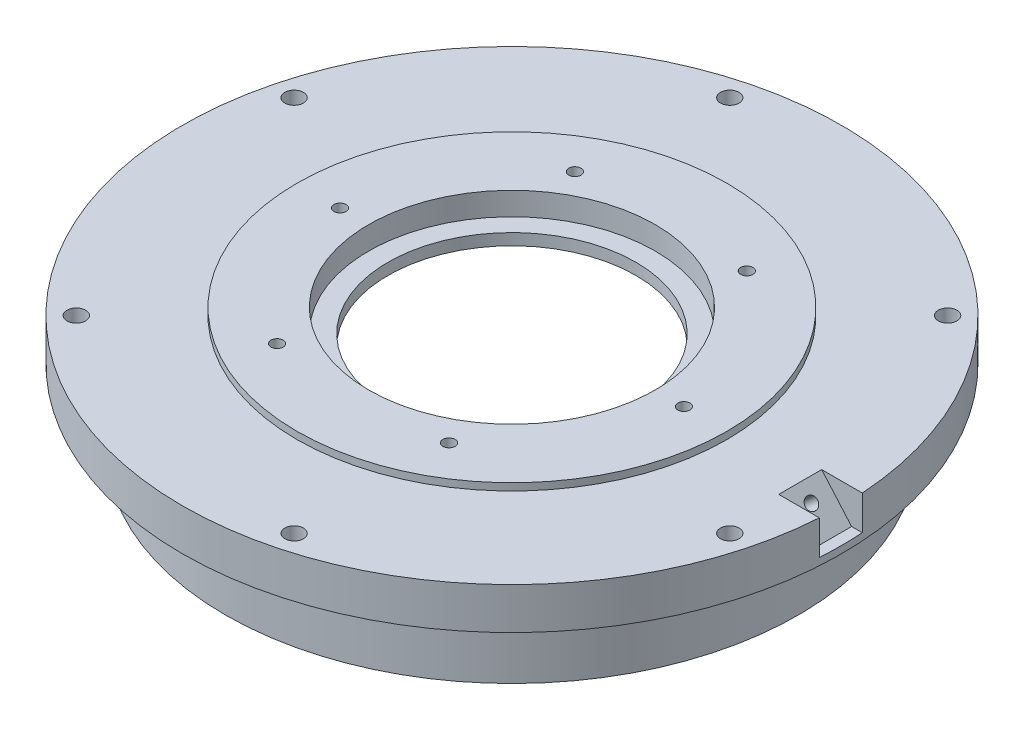
SolidWorks part; units mm, degrees
ref_plane "前视基准面" through (0, 0, 0) normal (0, 0, 1) x (1, 0, 0)
ref_plane "上视基准面" through (0, 0, 0) normal (0, 1, 0) x (1, 0, 0)
ref_plane "右视基准面" through (0, 0, 0) normal (1, 0, 0) x (0, 0, -1)
sketch "草图1" plane through (0, 0, 0) normal (0, 0, 1) x (1, 0, 0)
  line L0 (0, 0) -> (0, -65.2646) construction
  line L1 (-150, 0) -> (-100, 0)
  line L2 (-100, 0) -> (-100, -16)
  line L3 (-100, -16) -> (-86.5, -16)
  line L4 (-86.5, -16) -> (-86.5, -24)
  line L5 (-86.5, -24) -> (-170, -24)
  line L6 (-170, -24) -> (-190, -44)
  line L7 (-190, -44) -> (-190, -54.5)
  line L8 (-190, -54.5) -> (-180, -54.5)
  line L9 (-180, -54.5) -> (-180, -76)
  line L10 (-180, -76) -> (-195, -76)
  line L11 (-195, -76) -> (-195, -86)
  line L12 (-195, -86) -> (-200, -86)
  line L13 (-200, -86) -> (-200, -34)
  line L14 (-200, -34) -> (-230, -34)
  line L15 (-230, -34) -> (-230, -5)
  line L16 (-230, -5) -> (-150, -5)
  line L17 (-150, -5) -> (-150, 0)
  dimension "D1" = 173
  dimension "D2" = 200
  dimension "D3" = 300
  dimension "D4" = 340
  dimension "D5" = 380
  dimension "D6" = 360
  dimension "D7" = 390
  dimension "D8" = 400
  dimension "D9" = 86
  dimension "D10" = 81
  dimension "D11" = 21.5
  dimension "D12" = 10
  dimension "D13" = 16
  dimension "D14" = 52
  dimension "D15" = 460
  dimension "D16" = 8
  dimension "D17" = 45
revolve "旋转1" add sketch "草图1" angle 360 about L0
sketch "草图2" plane through (0, 0, 0) normal (0, 0, 1) x (1, 0, 0)
  line L0 (201.1764, -5) -> (222.0393, -29)
  line L1 (230, -5) -> (-230, -5) construction
  line L2 (222.0393, -29) -> (230, -29)
  line L3 (230, -34) -> (230, -5) construction
  line L4 (209, 38.8368) -> (209, -117.7206) construction
  line L5 (181.227, -14) -> (288.4451, -14) construction
  line L6 (201.1764, -5) -> (230, -5)
  line L7 (230, -5) -> (230, -29)
  point P12 (209, -14)
  dimension "D1" = 24
  dimension "D2" = 21
  dimension "D3" = 41
  dimension "D4" = 9
extrude "切除-拉伸1" cut sketch "草图2" against normal mid plane 30
sketch "草图3" plane through (0, 0, 0) normal (0, 1, 0) x (1, 0, 0)
  circle A0 centre (120, 0) radius 4.25
  circle A1 centre (0, 0) radius 120 construction
  dimension "D1" = 240
  dimension "D2" = 8.5
extrude "切除-拉伸2" cut sketch "草图3" against normal blind 20
pattern_circular "阵列(圆周)1" count 6 over 360 about axis through (0, 0, 0) along (0, 1, 0) of "切除-拉伸2"
sketch "草图4" plane through (0, -5, 0) normal (0, 1, 0) x (1, 0, 0)
  line L0 (0, 0) -> (55.6461, -207.6741) construction
  line L1 (0, 0) -> (0, -303.9055) construction
  circle A0 centre (0, 0) radius 215 construction
  circle A1 centre (55.6461, -207.6741) radius 6.5
  dimension "D1" = 430
  dimension "D2" = 15
  dimension "D3" = 13
extrude "切除-拉伸3" cut sketch "草图4" against normal up to next
pattern_circular "阵列(圆周)2" count 6 over 360 about axis through (0, 0, 0) along (0, 1, 0) of "切除-拉伸3"
sketch "草图5" plane through (112.1117, 97.4572, 0) normal (0.7547, 0.6561, 0) x (0, 0, -1)
  circle A0 centre (0, -147.6823) radius 4.25
  point P4 (0, 0)
  dimension "D1" = 8.5
extrude "切除-拉伸4" cut sketch "草图5" against normal blind 20
sketch "草图6" plane through (112.1117, 97.4572, 0) normal (0.7547, 0.6561, 0) x (0, 0, -1)
  circle A0 centre (0, -147.6823) radius 4
  dimension "D1" = 8
extrude "切除-拉伸5" cut sketch "草图6" against normal up to next
